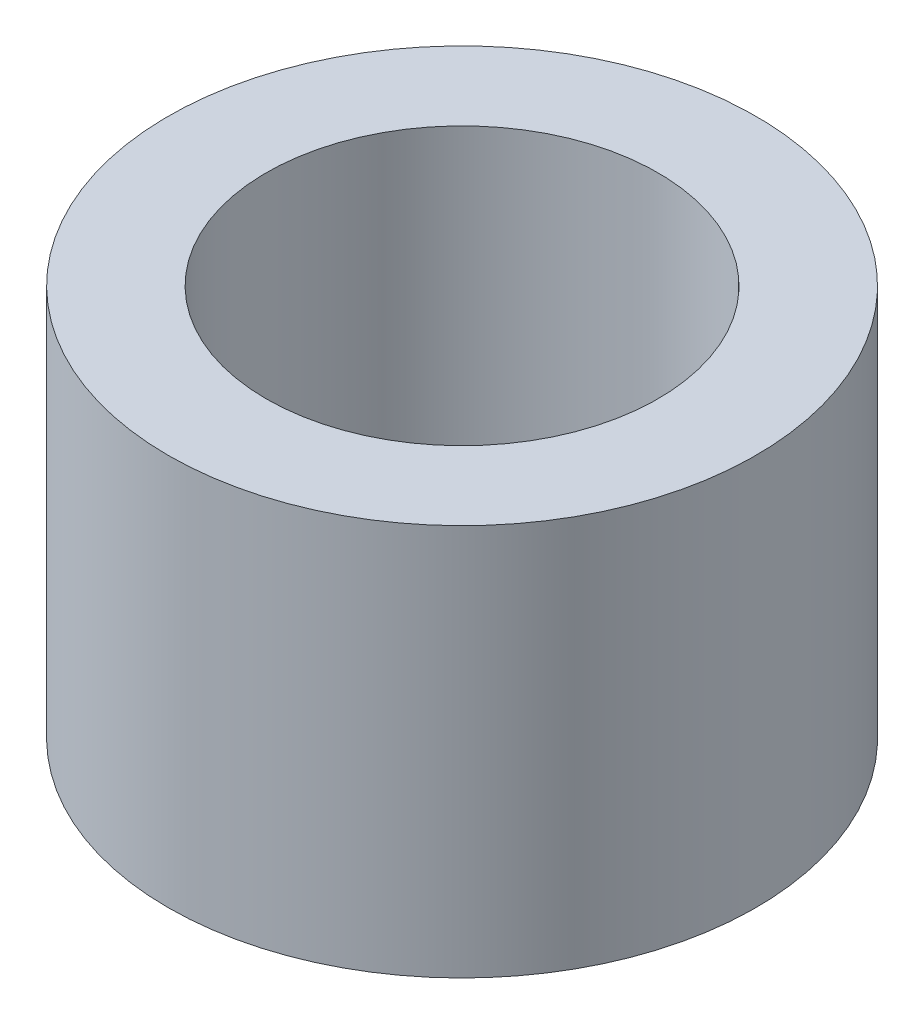
SolidWorks part; units mm, degrees
ref_plane "Front Plane" through (0, 0, 0) normal (0, 0, 1) x (1, 0, 0)
ref_plane "Top Plane" through (0, 0, 0) normal (0, 1, 0) x (1, 0, 0)
ref_plane "Right Plane" through (0, 0, 0) normal (1, 0, 0) x (0, 0, -1)
sketch "Sketch1" plane through (0, 0, 0) normal (0, 1, 0) x (1, 0, 0)
  circle A0 centre (0, 0) radius 4.7625
  dimension "D1" = 9.525
extrude "Boss-Extrude1" add sketch "Sketch1" along normal blind 6.35
sketch "Sketch2" plane through (0, 6.35, 0) normal (0, 1, 0) x (1, 0, 0)
  circle A0 centre (0, 0) radius 3.175
  dimension "D1" = 6.35
extrude "Cut-Extrude1" cut sketch "Sketch2" against normal blind 6.35
